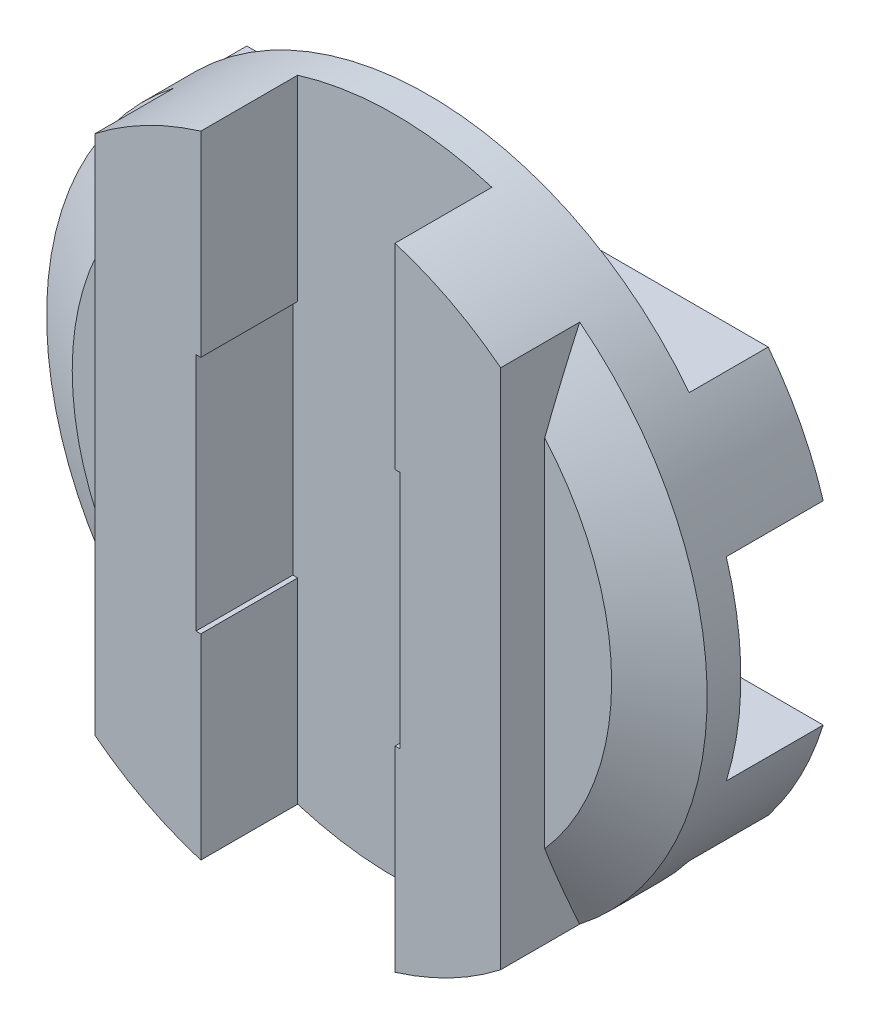
SolidWorks part; units mm, degrees
ref_plane "Front" through (0, 0, 0) normal (0, 0, 1) x (1, 0, 0)
ref_plane "Top" through (0, 0, 0) normal (0, 1, 0) x (1, 0, 0)
ref_plane "Right" through (0, 0, 0) normal (1, 0, 0) x (0, 0, -1)
sketch "Sketch1" plane through (0, 0, 0) normal (0, 0, 1) x (1, 0, 0)
  circle A0 centre (0, 0) radius 9.525
  point P3 (0, 9.525)
  dimension "OD" = 19.05
extrude "Boss-Extrude1" add sketch "Sketch1" against normal mid plane 6.0452
sketch "Sketch2" plane through (0, 0, 3.0226) normal (0, 0, 1) x (1, 0, 0)
  line L0 (-2.8004, 9.525) -> (2.8003, -9.525) construction
  line L1 (-2.8004, 9.525) -> (2.8003, 9.525)
  line L2 (-2.8004, 9.525) -> (-2.8003, -9.525)
  line L3 (-2.8003, -9.525) -> (2.8003, -9.525)
  line L4 (2.8003, 9.525) -> (2.8003, -9.525)
  circle A0 centre (0, 0) radius 9.525 construction
  dimension "Tooth gap" = 5.6007
extrude "Cut-Extrude1" cut sketch "Sketch2" against normal blind 2.794
sketch "Sketch3" plane through (0, 0, -3.0226) normal (0, 0, -1) x (-1, 0, 0)
  line L1 (-9.525, 2.8004) -> (9.525, 2.8004)
  line L2 (-9.525, 2.8004) -> (-9.525, -2.8003)
  line L3 (-9.525, -2.8003) -> (9.525, -2.8003)
  line L4 (9.525, 2.8004) -> (9.525, -2.8003)
  line L14 (2.8004, 9.525) -> (-2.8003, 9.525) construction
  line L15 (9.525, 2.8004) -> (-9.525, -2.8003) construction
  circle A0 centre (0, 0) radius 9.525 construction
extrude "Cut-Extrude2" cut sketch "Sketch3" against normal blind 2.794
sketch "Sketch4" plane through (0, 0, 3.0226) normal (0, 0, 1) x (1, 0, 0)
  line L0 (-2.8004, 0) -> (-5.8484, 0) construction
  line L1 (9.525, 9.525) -> (5.8484, 9.525)
  line L2 (9.525, 9.525) -> (9.525, -9.525)
  line L3 (9.525, -9.525) -> (5.8484, -9.525)
  line L4 (5.8484, 9.525) -> (5.8484, -9.525)
  line L5 (-9.525, 9.525) -> (-5.8484, 9.525)
  line L6 (-9.525, 9.525) -> (-9.525, -9.525)
  line L7 (-9.525, -9.525) -> (-5.8483, -9.525)
  line L8 (-5.8484, 9.525) -> (-5.8483, -9.525)
  line L9 (-2.8004, 9.104) -> (-2.8004, -9.104) construction
  line L10 (2.8003, 0) -> (5.8484, 0) construction
  line L11 (2.8003, -9.104) -> (2.8003, 9.104) construction
  line L12 (-2.8004, 9.525) -> (2.8003, 9.525) construction
  line L13 (-2.8003, -9.525) -> (2.8003, -9.525) construction
  line L14 (2.8003, 9.525) -> (2.8003, -9.525) construction
  circle A1 centre (0, 0) radius 9.525 construction
  dimension "D1" = 3.6766
  dimension "Tooth thickness" = 3.048
extrude "Cut-Extrude3" cut sketch "Sketch4" against normal blind 1.27
sketch "Sketch5" plane through (0, 0, -3.0226) normal (0, 0, -1) x (-1, 0, 0)
  line L0 (-9.525, 9.525) -> (-5.8484, 9.525) construction
  line L1 (-9.525, 9.525) -> (9.525, 9.525)
  line L2 (-9.525, 9.525) -> (-9.525, 5.8484)
  line L3 (-9.525, 5.8484) -> (9.525, 5.8484)
  line L4 (9.525, 9.525) -> (9.525, 5.8484)
  line L5 (9.525, -9.525) -> (-9.525, -9.525)
  line L6 (9.525, -9.525) -> (9.525, -5.8483)
  line L7 (9.525, -5.8483) -> (-9.525, -5.8483)
  line L8 (-9.525, -9.525) -> (-9.525, -5.8483)
  line L9 (0, 2.8004) -> (0, 5.8484) construction
  line L10 (-9.104, 2.8004) -> (9.104, 2.8004) construction
  line L11 (-9.525, 2.8004) -> (-9.525, -2.8003) construction
  line L12 (0, -5.8483) -> (0, -2.8003) construction
  line L13 (-9.104, -2.8003) -> (9.104, -2.8003) construction
  circle A0 centre (0, 0) radius 9.525 construction
extrude "Cut-Extrude4" cut sketch "Sketch5" against normal blind 1.27
chamfer "Chamfer1" distance 1.7464 angle 30 4 edges at (0, -9.525, -1.7526) (0, 9.525, -1.7526) (-9.525, 0, 1.7526) (9.525, 0, 1.7526)
sketch "Sketch6" plane through (0, 0, 3.0226) normal (0, 0, 1) x (1, 0, 0)
  line L0 (-2.9404, 3.4528) -> (2.9404, -3.4528) construction
  line L1 (-2.9404, 3.4528) -> (2.9404, 3.4528)
  line L2 (-2.9404, 3.4528) -> (-2.9404, -3.4528)
  line L3 (-2.9404, -3.4528) -> (2.9404, -3.4528)
  line L4 (2.9404, 3.4528) -> (2.9404, -3.4528)
  dimension "D1" = 5.8807
  dimension "D2" = 6.9056
extrude "Cut-Extrude5" cut sketch "Sketch6" against normal up to surface (2.794 mm away) up to face at (0, 0, 0.2286)
sketch "Sketch7" plane through (0, 0, -3.0226) normal (0, 0, -1) x (-1, 0, 0)
  line L0 (-3.4528, 2.9404) -> (3.4528, -2.9404) construction
  line L1 (-3.4528, 2.9404) -> (3.4528, 2.9404)
  line L2 (-3.4528, 2.9404) -> (-3.4528, -2.9404)
  line L3 (-3.4528, -2.9404) -> (3.4528, -2.9404)
  line L4 (3.4528, 2.9404) -> (3.4528, -2.9404)
  line L5 (2.9404, 3.4528) -> (2.9404, -3.4528) construction
  line L6 (2.9404, 3.4528) -> (-2.9404, 3.4528) construction
extrude "Cut-Extrude6" cut sketch "Sketch7" against normal up to surface (2.794 mm away) up to face at (0, 0, -0.2286)
sketch "Sketch8" plane through (0, 0, 0) normal (1, 0, 0) x (0, 0, -1)
  line L0 (-3.0226, 9.104) -> (-3.0226, 3.4528) construction
  line L2 (3.0226, 2.8004) -> (3.0226, 5.8484) construction
  point P0 (3.0226, 9.525)
  point P1 (-3.0226, 9.525)
equation "\"D1@Cut-Extrude2\" = \"Tooth depth@Cut-Extrude1\""
equation "\"D1@Cut-Extrude4\" = \"Tooth depth 2@Cut-Extrude3\""
equation "\"D1@Chamfer1\" = \"D1@Sketch4\" * .475"
equation "\"D1@Sketch6\" = \"Tooth gap@Sketch2\" * 1.05"
equation "\"D2@Sketch6\" = \"OD@Sketch1\" * .3625"
